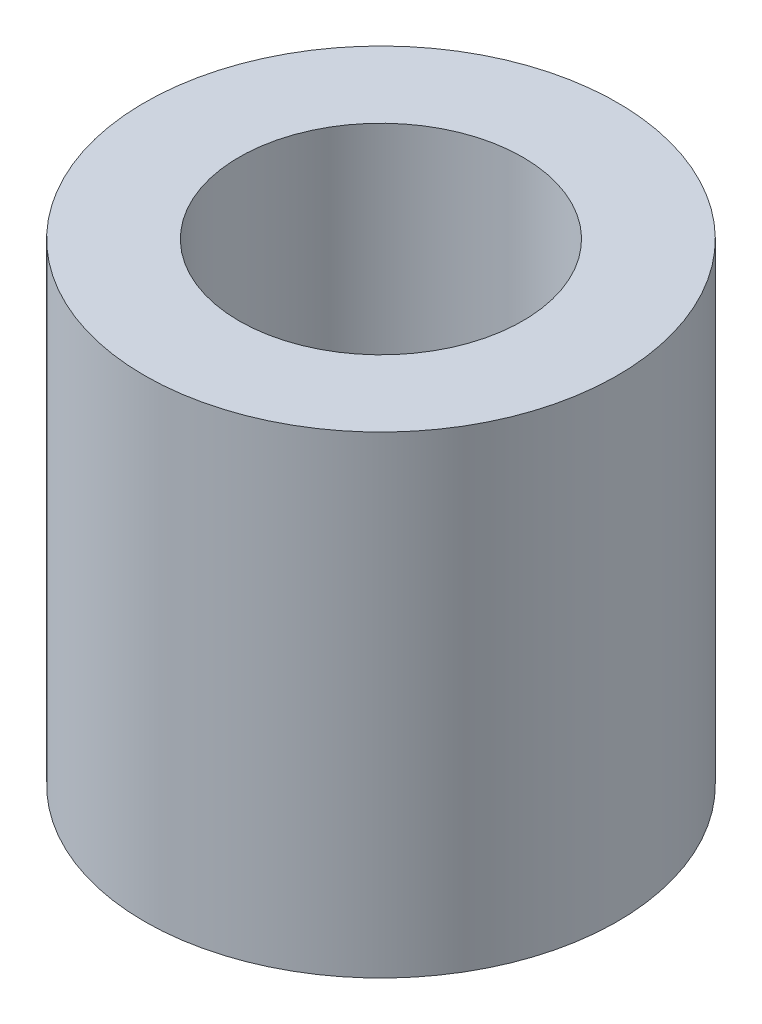
SolidWorks part; units mm, degrees
material "PET"
ref_plane "前视基准面" through (0, 0, 0) normal (0, 0, 1) x (1, 0, 0)
ref_plane "上视基准面" through (0, 0, 0) normal (0, 1, 0) x (1, 0, 0)
ref_plane "右视基准面" through (0, 0, 0) normal (1, 0, 0) x (0, 0, -1)
other "Configuration Table"
sketch "草图1" plane through (0, 0, 0) normal (0, 1, 0) x (1, 0, 0)
  circle A0 centre (0, 0) radius 5
  circle A1 centre (0, 0) radius 3
  dimension "D1" = 6
  dimension "D2" = 10
extrude "凸台-拉伸1" add sketch "草图1" along normal blind 10
